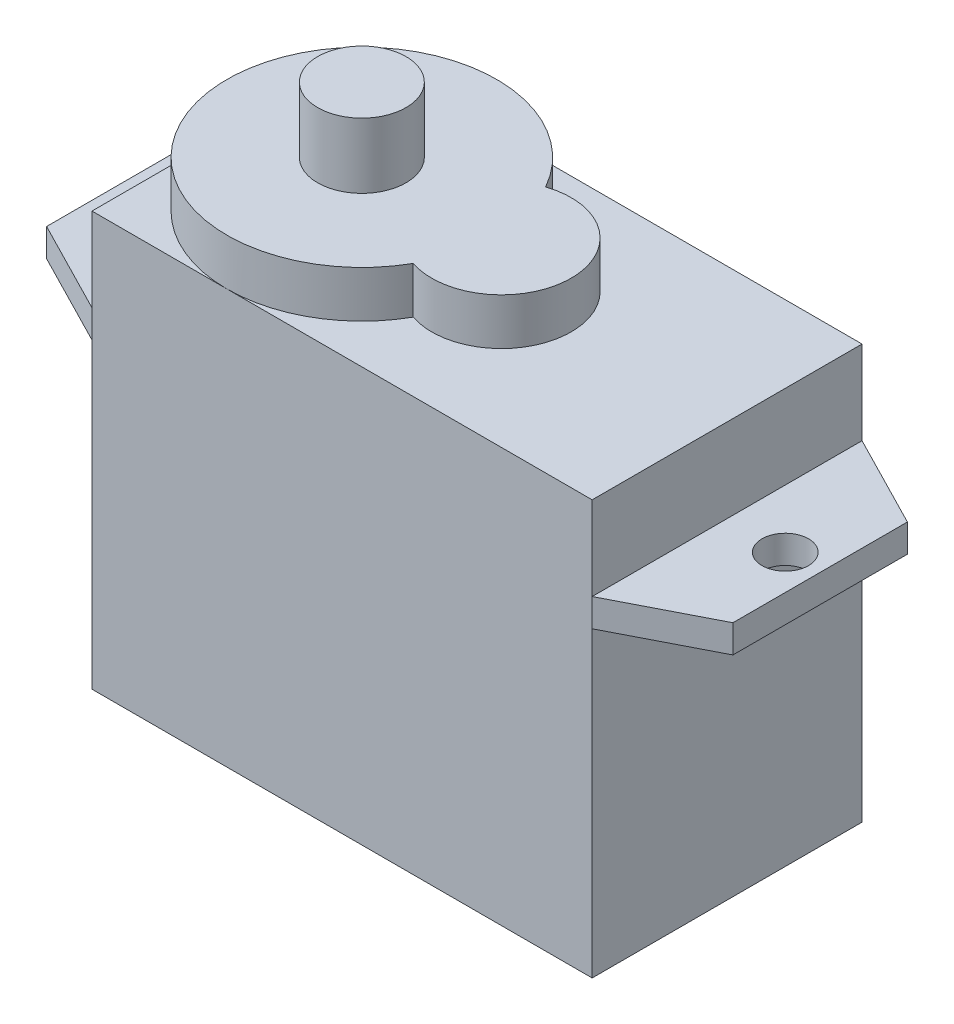
SolidWorks part; units mm, degrees
ref_plane "Front Plane" through (0, 0, 0) normal (0, 0, 1) x (1, 0, 0)
ref_plane "Top Plane" through (0, 0, 0) normal (0, 1, 0) x (1, 0, 0)
ref_plane "Right Plane" through (0, 0, 0) normal (1, 0, 0) x (0, 0, -1)
sketch "Sketch1" plane through (0, 0, 0) normal (0, 1, 0) x (1, 0, 0)
  line L1 (-10.75, 5.8) -> (10.75, 5.8)
  line L2 (-10.75, 5.8) -> (-10.75, -5.8)
  line L3 (-10.75, -5.8) -> (10.75, -5.8)
  line L4 (10.75, 5.8) -> (10.75, -5.8)
  line L5 (-10.75, 5.8) -> (10.75, -5.8) construction
  line L6 (-10.75, -5.8) -> (10.75, 5.8) construction
  point P0 (0, 0)
  dimension "D1" = 11.6
  dimension "D2" = 21.5
extrude "Boss-Extrude1" add sketch "Sketch1" along normal blind 13
sketch "Sketch2" plane through (0, 13, 0) normal (0, 1, 0) x (1, 0, 0)
  line L0 (-10.75, 5.8) -> (-14.75, 3.75)
  line L1 (-14.75, 3.75) -> (-14.75, -3.75)
  line L2 (-14.75, -3.75) -> (-10.75, -5.8)
  line L3 (0, 5.8) -> (0, -5.8) construction
  line L4 (10.75, -5.8) -> (10.75, 5.8)
  line L5 (10.75, 5.8) -> (-10.75, 5.8)
  line L6 (-10.75, 5.8) -> (-10.75, -5.8)
  line L7 (-10.75, -5.8) -> (10.75, -5.8)
  line L9 (10.75, 5.8) -> (-10.75, 5.8)
  line L11 (-10.75, -5.8) -> (10.75, -5.8)
  line L12 (10.75, 5.8) -> (14.75, 3.75)
  line L13 (14.75, -3.75) -> (10.75, -5.8)
  line L14 (14.75, 3.75) -> (14.75, -3.75)
  line L15 (-14.75, 0) -> (14.75, 0) construction
  line L16 (-10.75, 5.8) -> (-10.75, -5.8) construction
  circle A0 centre (-13.25, 0) radius 1
  circle A1 centre (13.25, 0) radius 1
  point P8 (-14.75, 0)
  dimension "D3" = 2
  dimension "D2" = 7.5
  dimension "D4" = 2.5
  dimension "D1" = 0
extrude "Boss-Extrude2" add sketch "Sketch2" along normal blind 1.2
sketch "Sketch3" plane through (0, 14.2, 0) normal (0, 1, 0) x (1, 0, 0)
  line L1 (-10.75, 5.8) -> (10.75, 5.8)
  line L2 (-10.75, 5.8) -> (-10.75, -5.8)
  line L3 (-10.75, -5.8) -> (10.75, -5.8)
  line L4 (10.75, 5.8) -> (10.75, -5.8)
extrude "Boss-Extrude3" add sketch "Sketch3" along normal blind 3.6
sketch "Sketch4" plane through (0, 17.8, 0) normal (0, 1, 0) x (1, 0, 0)
  line L0 (-10.75, 0) -> (10.75, 0) construction
  line L1 (-10.75, 5.8) -> (-10.75, -5.8) construction
  line L2 (10.75, -5.8) -> (10.75, 5.8) construction
  arc A1 (0.1033, 2.8467) -> (0.1033, -2.8467) centre (-4.95, 0) ccw
  arc A2 (0.1033, -2.8467) -> (0.1033, 2.8467) centre (1.05, 0) ccw
  dimension "D2" = 6
  dimension "D1" = 5.8
  dimension "D3" = 6
extrude "Boss-Extrude4" add sketch "Sketch4" along normal blind 2
sketch "Sketch5" plane through (0, 19.8, 0) normal (0, 1, 0) x (1, 0, 0)
  circle A0 centre (-4.95, 0) radius 1.9
  dimension "D1" = 3.8
extrude "Boss-Extrude5" add sketch "Sketch5" along normal blind 2.8
